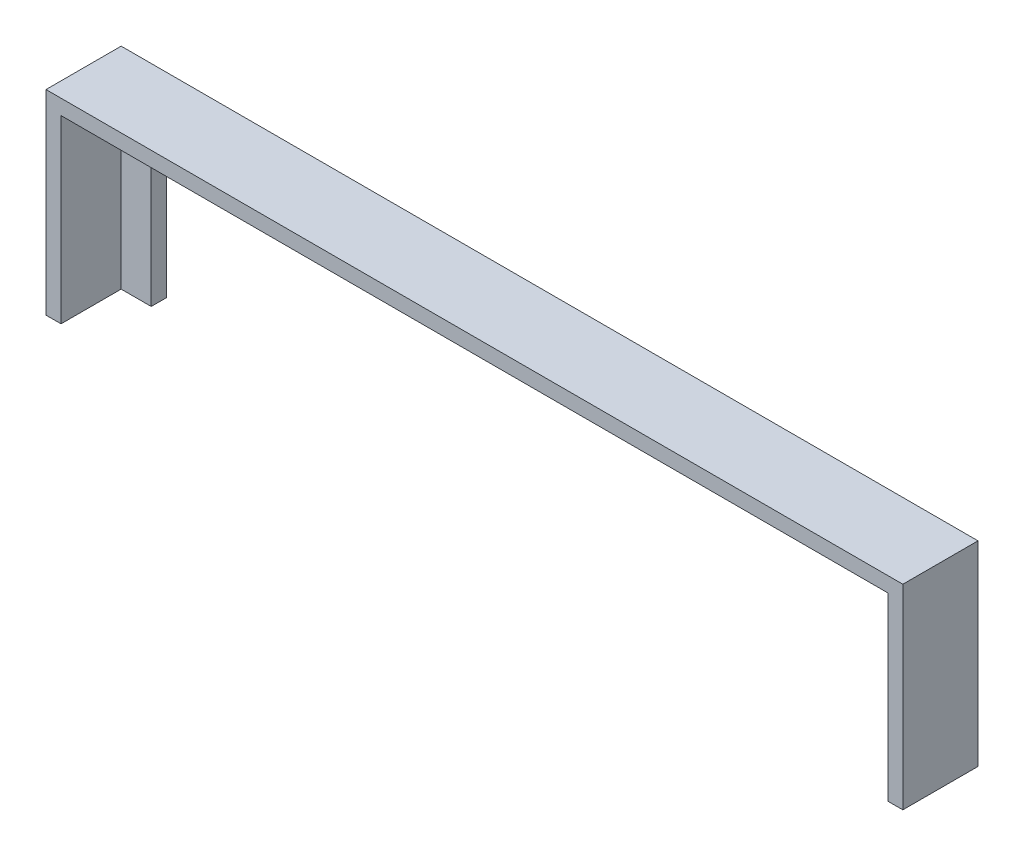
SolidWorks part; units mm, degrees
ref_plane "Alzado" through (0, 0, 0) normal (0, 0, 1) x (1, 0, 0)
ref_plane "Planta" through (0, 0, 0) normal (0, 1, 0) x (1, 0, 0)
ref_plane "Vista lateral" through (0, 0, 0) normal (1, 0, 0) x (0, 0, -1)
sketch "Croquis1" plane through (0, 0, 0) normal (0, 0, 1) x (1, 0, 0)
  line L0 (-71.8414, -5.7083) -> (-71.8414, 4.2917)
  line L1 (-71.8414, 4.2917) -> (-20.8414, 4.2917)
  line L2 (-20.8414, 4.2917) -> (-20.8414, -5.7083)
  line L3 (-20.8414, -5.7083) -> (-17.8414, -5.7083)
  line L4 (-17.8414, -5.7083) -> (-17.8414, 7.2917)
  line L5 (-17.8414, 7.2917) -> (-74.8414, 7.2917)
  line L6 (-74.8414, 7.2917) -> (-74.8414, -5.7083)
  line L7 (-74.8414, -5.7083) -> (-71.8414, -5.7083)
extrude "Saliente-Extruir1" add sketch "Croquis1" along normal blind 5
sketch "Croquis2" plane through (0, 0, 5) normal (0, 0, 1) x (1, 0, 0)
  line L0 (-71.8414, -5.7083) -> (-73.8414, -5.7083)
  line L1 (-74.8414, -5.7083) -> (-71.8414, -5.7083) construction
  line L2 (-73.8414, -5.7083) -> (-73.8414, 6.2917)
  line L3 (-73.8414, 6.2917) -> (-18.8414, 6.2917)
  line L4 (-18.8414, 6.2917) -> (-18.8414, -5.7083)
  line L5 (-20.8414, -5.7083) -> (-17.8414, -5.7083) construction
  line L6 (-18.8414, -5.7083) -> (-20.8414, -5.7083)
  line L7 (-20.8414, -5.7083) -> (-20.8414, 4.2917)
  line L8 (-20.8414, 4.2917) -> (-71.8414, 4.2917)
  line L9 (-71.8414, 4.2917) -> (-71.8414, -5.7083)
extrude "Cortar-Extruir1" cut sketch "Croquis2" against normal blind 4
